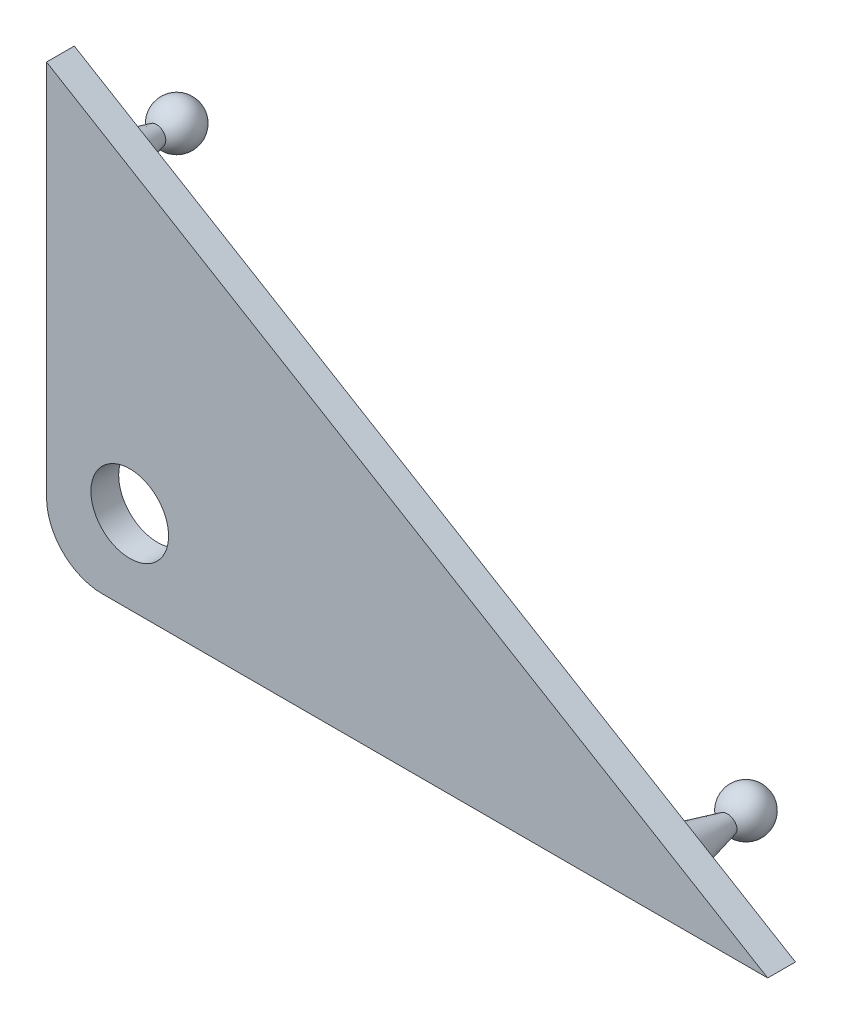
SolidWorks part; units mm, degrees
material "201.0-T6, per stampo in conchiglia (SS)"
ref_plane "Piano frontale" through (0, 0, 0) normal (0, 0, 1) x (1, 0, 0)
ref_plane "Piano superiore" through (0, 0, 0) normal (0, 1, 0) x (1, 0, 0)
ref_plane "Piano destro" through (0, 0, 0) normal (1, 0, 0) x (0, 0, -1)
sketch "Schizzo1" plane through (0, 0, 0) normal (0, 0, 1) x (1, 0, 0)
  line L0 (0, 0) -> (0, 78)
  line L1 (0, 78) -> (130, 0)
  line L2 (130, 0) -> (0, 0)
  dimension "D1" = 78
  dimension "D2" = 130
extrude "Estrusione-Estrusione1" add sketch "Schizzo1" along normal blind 5
sketch "Schizzo2" plane through (0, 0, 0) normal (0, 0, -1) x (-1, 0, 0)
  line L0 (0, 78) -> (0, 0) construction
  line L1 (0, 0) -> (-130, 0) construction
  circle A0 centre (-15, 15) radius 7
  dimension "D1" = 15
  dimension "D2" = 15
extrude "Taglio-Estrusione1" cut sketch "Schizzo2" against normal through all
fillet "Raccordo1" radius 10 1 edges at (0, 0, 2.5)
sketch "Schizzo3" plane through (0, 0, 5) normal (0, 0, 1) x (1, 0, 0)
  line L0 (0, 78) -> (0, 10) construction
  line L1 (130, 0) -> (0, 78) construction
  circle A0 centre (5.464, 62.1376) radius 4
  dimension "D1" = 5.464
  dimension "D2" = 10.7907
sketch "Schizzo6" plane through (0, 0, 5) normal (0, 0, 1) x (1, 0, 0)
  line L0 (130, 0) -> (0, 78) construction
  line L1 (10, 0) -> (130, 0) construction
  circle A0 centre (108.3381, 6) radius 4
  dimension "D1" = 6
  dimension "D2" = 6
sketch "Schizzo10" plane through (0, 0, 0) normal (0, 0, -1) x (-1, 0, 0)
  circle A0 centre (-5.464, 62.1376) radius 4 construction
  circle A1 centre (-5.464, 62.1376) radius 4
extrude "Estrusione-Estrusione2" add sketch "Schizzo10" along normal blind 10 draft 14
sketch "Schizzo11" plane through (0, 0, -10) normal (0, 0, -1) x (-1, 0, 0)
  point P0 (-5.464, 62.1376)
ref_plane "Piano1" through (5.464, 0, 0) normal (-1, 0, 0) x (0, 0, 1)
sketch "Schizzo12" plane through (5.464, 0, 0) normal (-1, 0, 0) x (0, 0, 1)
  line L0 (-13, 58.1376) -> (-13, 66.1376)
  line L1 (-10, 63.6443) -> (-10, 60.6309) construction
  arc A0 (-13, 58.1376) -> (-13, 66.1376) centre (-13, 62.1376) ccw
  dimension "D1" = 8
  dimension "D2" = 3
revolve "Rivoluzione1" add sketch "Schizzo12" angle 360 about L0
sketch "Schizzo13" plane through (0, 0, 0) normal (0, 0, -1) x (-1, 0, 0)
  circle A0 centre (-108.3381, 6) radius 4 construction
  circle A1 centre (-108.3381, 6) radius 4
extrude "Estrusione-Estrusione3" add sketch "Schizzo13" along normal blind 10 draft 14
sketch "Schizzo14" plane through (0, 0, -10) normal (0, 0, -1) x (-1, 0, 0)
  point P0 (-108.3381, 6)
ref_plane "Piano2" through (31.3248, 52.208, 0) normal (0.5145, 0.8575, 0) x (0.8575, -0.5145, 0)
sketch "Schizzo15" plane through (31.3248, 52.208, 0) normal (0.5145, 0.8575, 0) x (0.8575, -0.5145, 0)
  line L0 (85.5084, 13) -> (93.5084, 13)
  line L1 (91.3189, 10) -> (88.3055, 10) construction
  arc A0 (85.5084, 13) -> (93.5084, 13) centre (89.5084, 13) ccw
  dimension "D1" = 8
  dimension "D2" = 3
revolve "Rivoluzione2" add sketch "Schizzo15" angle 360 about L0
